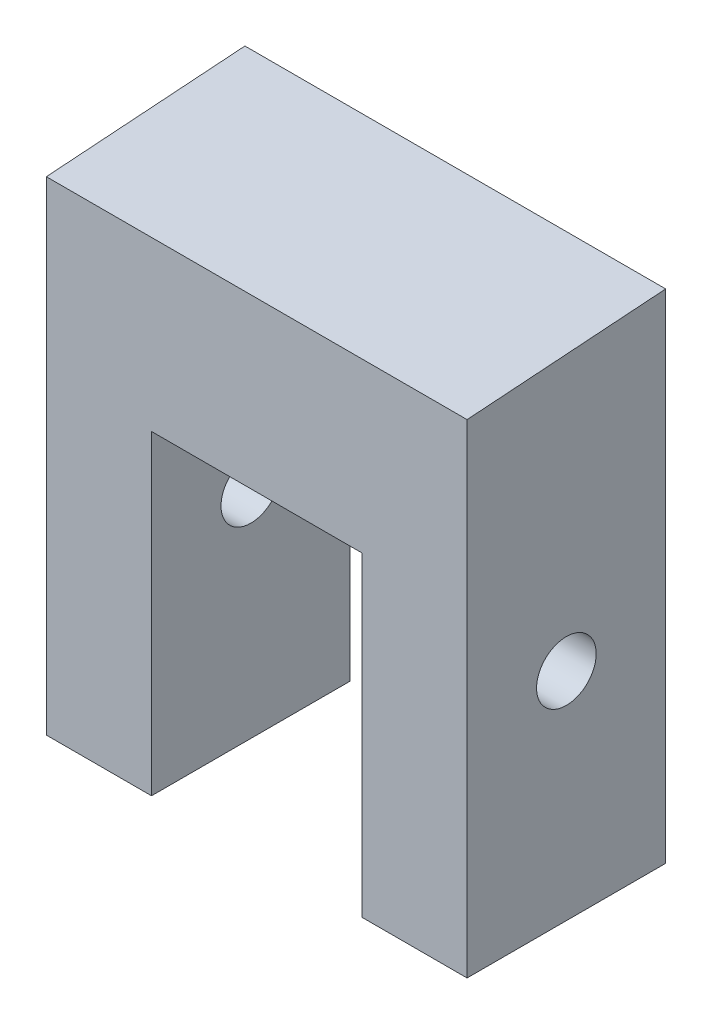
SolidWorks part; units mm, degrees
ref_plane "Front Plane" through (0, 0, 0) normal (0, 0, 1) x (1, 0, 0)
ref_plane "Top Plane" through (0, 0, 0) normal (0, 1, 0) x (1, 0, 0)
ref_plane "Right Plane" through (0, 0, 0) normal (1, 0, 0) x (0, 0, -1)
sketch "Sketch1" plane through (0, 0, 0) normal (1, 0, 0) x (0, 0, -1)
  line L0 (0, 0) -> (11.9888, 0)
  line L1 (11.9888, 0) -> (11.9888, 30.0328)
  line L2 (11.9888, 30.0328) -> (0, 29.1944)
  line L3 (0, 29.1944) -> (0, 0)
  line L4 (0, 15.5448) -> (11.9888, 15.5448) construction
  line L5 (0, 29.1944) -> (-195.199, 15.5448) construction
  line L6 (-195.199, 15.5448) -> (0, 15.5448) construction
  dimension "D1" = 4
  dimension "D2" = 11.9888
  dimension "D3" = 207.1878
  dimension "D4" = 15.5448
extrude "Boss-Extrude1" add sketch "Sketch1" along normal blind 25.4
sketch "Sketch2" plane through (0, 0, 0) normal (0, 0, 1) x (1, 0, 0)
  line L0 (25.4, 0) -> (0, 0) construction
  line L1 (6.35, 19.05) -> (19.05, 19.05)
  line L2 (6.35, 19.05) -> (6.35, 0)
  line L3 (6.35, 0) -> (19.05, 0)
  line L4 (19.05, 19.05) -> (19.05, 0)
  line L5 (6.35, 19.05) -> (19.05, 0) construction
  line L6 (6.35, 0) -> (19.05, 19.05) construction
  point P0 (12.7, 9.525)
  point P7 (12.7, 0)
  dimension "D1" = 19.05
  dimension "D2" = 12.7
extrude "Cut-Extrude1" cut sketch "Sketch2" against normal through all
hole_wizard "M3 Clearance Hole1" positions "Sketch3" profile "Sketch4" hole size "M3" standard "ANSI Metric" end condition through all
sketch "Sketch3" plane through (25.4, 0, 0) normal (1, 0, 0) x (0, 0, -1)
  line L0 (11.9888, 19.05) -> (0, 19.05) construction
  line L2 (11.9888, 0) -> (11.9888, 30.0328) construction
  point P0 (5.9944, 13.0556)
  dimension "D1" = 5.9944
  dimension "D2" = 5.9944
sketch "Sketch4" plane through (25.4, 13.0556, -5.9944) normal (0, 1, 0) x (0, 0, -1)
  line L0 (0, 0) -> (0, 25.4)
  line L1 (0, 25.4) -> (1.8, 25.4)
  line L2 (1.8, 25.4) -> (1.8, 0)
  line L5 (1.8, 0) -> (0, 0)
  line L11 (0, -6.35) -> (0, 107.95) construction
  dimension "Thru Hole Dia." = 3.6
  dimension "Thru Hole Depth" = 25.4
